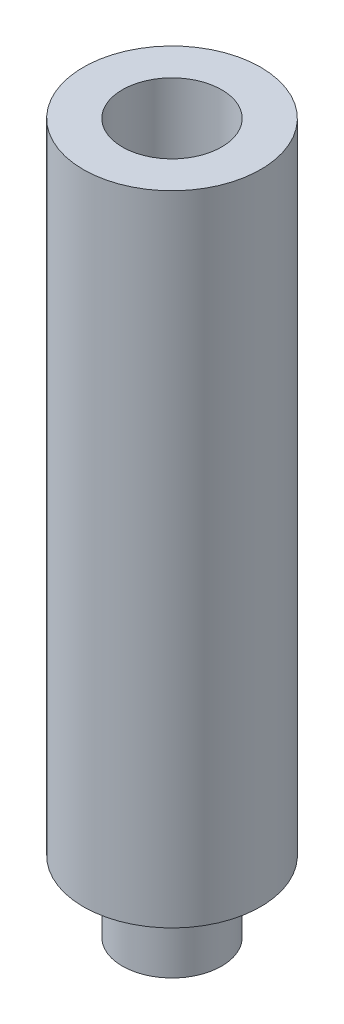
SolidWorks part; units mm, degrees
ref_plane "前视基准面" through (0, 0, 0) normal (0, 0, 1) x (1, 0, 0)
ref_plane "上视基准面" through (0, 0, 0) normal (0, 1, 0) x (1, 0, 0)
ref_plane "右视基准面" through (0, 0, 0) normal (1, 0, 0) x (0, 0, -1)
other "Configuration Table"
sketch "草图1" plane through (0, 0, 0) normal (0, 1, 0) x (1, 0, 0)
  circle A0 centre (0, 0) radius 1.4
  dimension "D1" = 2.8
extrude "凸台-拉伸1" add sketch "草图1" along normal blind 2
sketch "草图2" plane through (0, 2, 0) normal (0, 1, 0) x (1, 0, 0)
  circle A0 centre (0, 0) radius 2.5
  dimension "D1" = 5
extrude "凸台-拉伸2" add sketch "草图2" along normal blind 18
sketch "草图3" plane through (0, 20, 0) normal (0, 1, 0) x (1, 0, 0)
  circle A0 centre (0, 0) radius 1.4
  dimension "D1" = 2.8
extrude "切除-拉伸1" cut sketch "草图3" against normal blind 3
